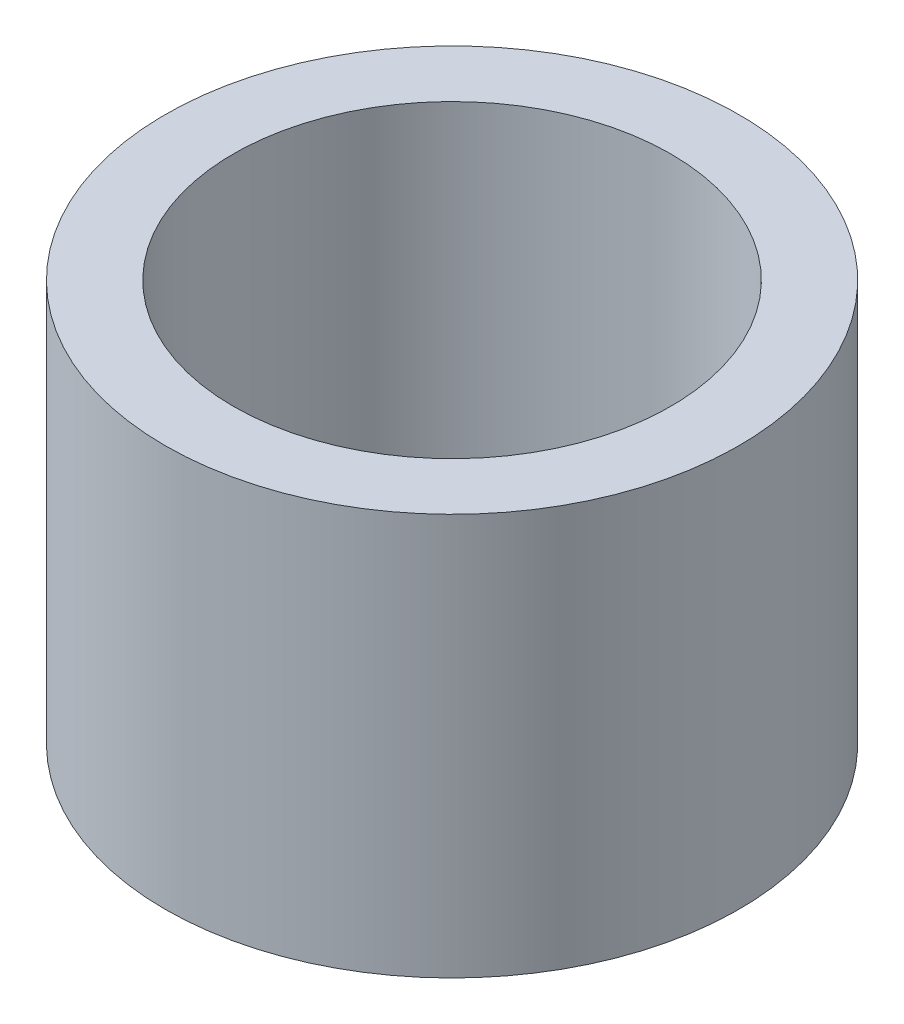
SolidWorks part; units mm, degrees
ref_plane "Front Plane" through (0, 0, 0) normal (0, 0, 1) x (1, 0, 0)
ref_plane "Top Plane" through (0, 0, 0) normal (0, 1, 0) x (1, 0, 0)
ref_plane "Right Plane" through (0, 0, 0) normal (1, 0, 0) x (0, 0, -1)
sketch "Sketch1" plane through (0, 0, 0) normal (0, 1, 0) x (1, 0, 0)
  circle A0 centre (0, 0) radius 3.05
  circle A1 centre (0, 0) radius 4
  dimension "D1" = 6.1
  dimension "D2" = 8
extrude "Boss-Extrude1" add sketch "Sketch1" along normal blind 5.6
